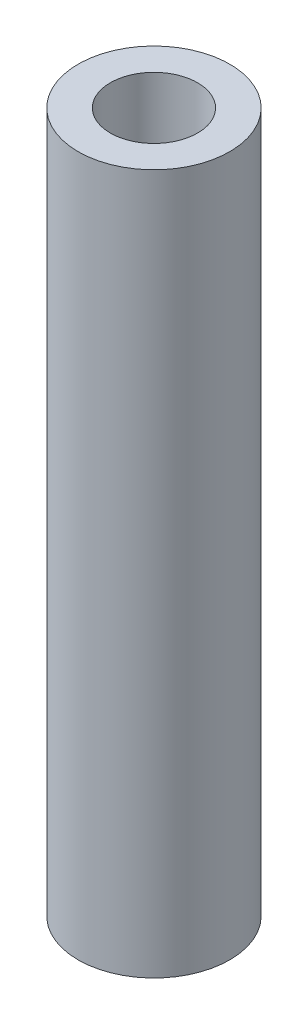
SolidWorks part; units mm, degrees
ref_plane "Front Plane" through (0, 0, 0) normal (0, 0, 1) x (1, 0, 0)
ref_plane "Top Plane" through (0, 0, 0) normal (0, 1, 0) x (1, 0, 0)
ref_plane "Right Plane" through (0, 0, 0) normal (1, 0, 0) x (0, 0, -1)
sketch "Sketch1" plane through (0, 0, 0) normal (0, 1, 0) x (1, 0, 0)
  circle A0 centre (0, 0) radius 5.65
  circle A1 centre (0, 0) radius 3.25
  dimension "D1" = 6.5
  dimension "D2" = 2.4
extrude "Boss-Extrude1" add sketch "Sketch1" along normal offset from surface 0.5 and the other way offset from surface (26.081 mm away) 0.5
